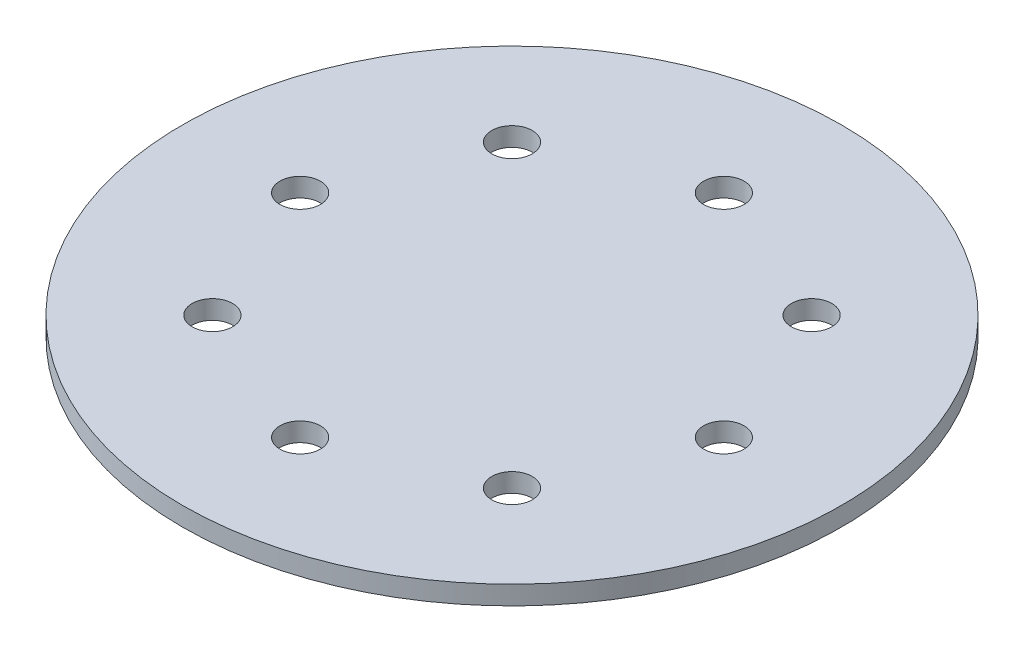
SolidWorks part; units mm, degrees
ref_plane "Front Plane" through (0, 0, 0) normal (0, 0, 1) x (1, 0, 0)
ref_plane "Top Plane" through (0, 0, 0) normal (0, 1, 0) x (1, 0, 0)
ref_plane "Right Plane" through (0, 0, 0) normal (1, 0, 0) x (0, 0, -1)
sketch "Sketch1" plane through (0, 0, 0) normal (0, 1, 0) x (1, 0, 0)
  circle A0 centre (0, 0) radius 35
  dimension "D1" = 70
extrude "Boss-Extrude1" add sketch "Sketch1" along normal blind 2
sketch "Sketch2" plane through (0, 2, 0) normal (0, 1, 0) x (1, 0, 0)
  line L0 (0, 0) -> (0, 22.5) construction
  line L1 (0, -1.1) -> (0, 1.1) construction
  circle A0 centre (0, 22.5) radius 2.15
  dimension "D2" = 4.3
  dimension "D1" = 22.5
extrude "Cut-Extrude1" cut sketch "Sketch2" against normal blind 2
pattern_circular "CirPattern1" count 8 over 360 about axis through (0, 0, 0) along (0, 1, 0) of "Cut-Extrude1"
